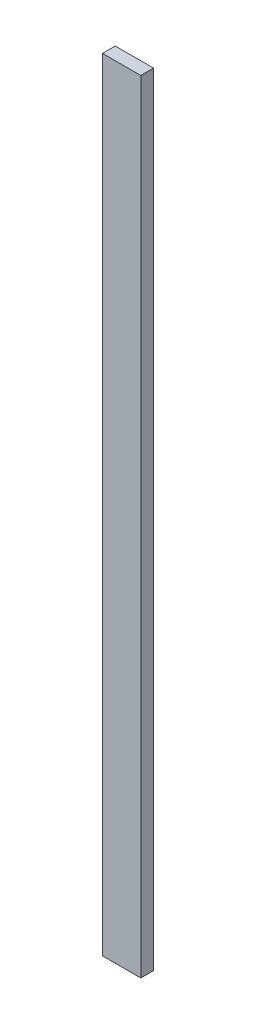
SolidWorks part; units mm, degrees
ref_plane "Front Plane" through (0, 0, 0) normal (0, 0, 1) x (1, 0, 0)
ref_plane "Top Plane" through (0, 0, 0) normal (0, 1, 0) x (1, 0, 0)
ref_plane "Right Plane" through (0, 0, 0) normal (1, 0, 0) x (0, 0, -1)
sketch "Sketch1" plane through (0, 0, 0) normal (0, 0, 1) x (1, 0, 0)
  line L1 (0, 0) -> (12, 0)
  line L2 (0, 0) -> (0, 245)
  line L3 (0, 245) -> (12, 245)
  line L4 (12, 0) -> (12, 245)
  dimension "D1" = 12
  dimension "D2" = 245
extrude "Profile" add sketch "Sketch1" along normal blind 4
equation "\"Profile_Depth\" = 4mm"
equation "\"D1@Profile\" = \"Profile_Depth\""
equation "\"EnvelopeWidth\" = 12mm"
equation "\"EnvelopeHeight\" = 245mm"
